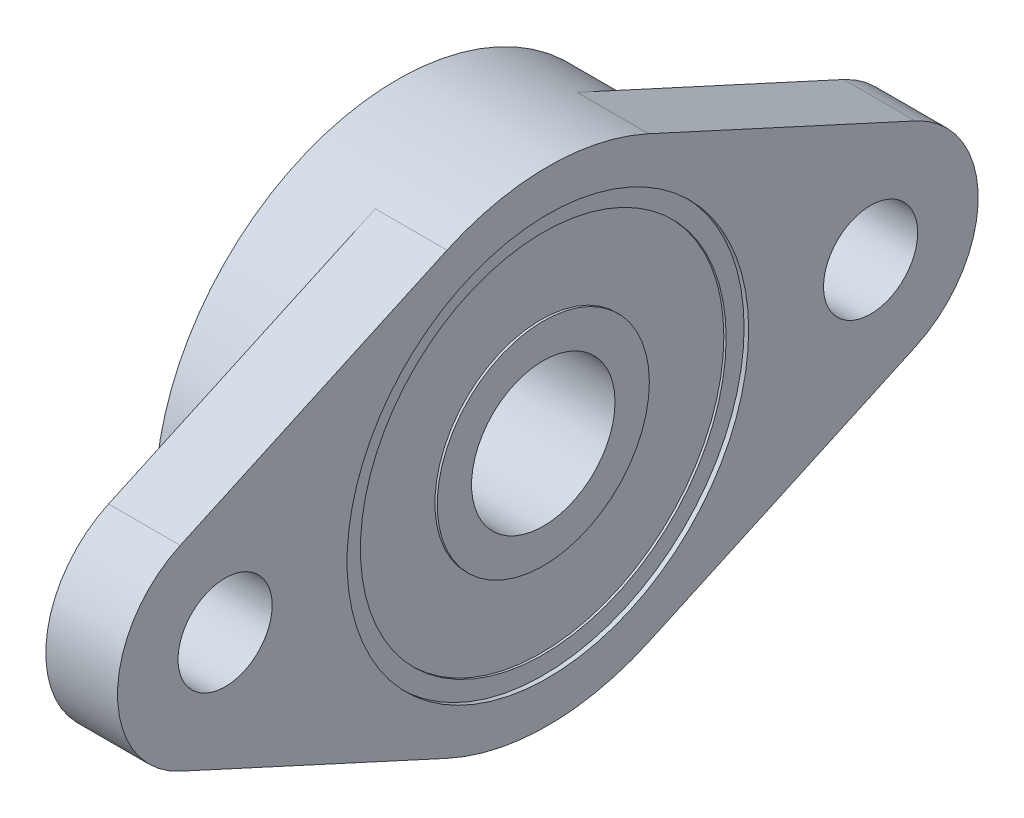
SolidWorks part; units mm, degrees
ref_plane "Front Plane" through (0, 0, 0) normal (0, 0, 1) x (1, 0, 0)
ref_plane "Top Plane" through (0, 0, 0) normal (0, 1, 0) x (1, 0, 0)
ref_plane "Right Plane" through (0, 0, 0) normal (1, 0, 0) x (0, 0, -1)
sketch "Sketch2" plane through (0, 0, 0) normal (0, 1, 0) x (1, 0, 0)
  line L0 (0, 0) -> (-21.1446, 0) construction
  line L1 (-0.2554, 4) -> (-11.7, 4)
  line L2 (-11.7, 4) -> (-11.7, 5.915)
  line L3 (-11.7, 5.915) -> (-7.6784, 5.915)
  line L4 (-7.6784, 5.915) -> (-7.6784, 10.2)
  line L5 (-7.6784, 10.2) -> (-7.9154, 10.2)
  line L6 (-7.9154, 10.2) -> (-7.9154, 11.2)
  line L7 (-7.9154, 11.2) -> (-8.1271, 11.2)
  line L8 (-8.1271, 11.2) -> (-8.4, 11.4729)
  line L9 (-8.4, 11.4729) -> (-8.4, 13.5)
  line L10 (-8.4, 13.5) -> (0, 13.5)
  line L12 (0, 0) -> (0, 13.5) construction
  line L13 (-7.6784, 5.915) -> (4.6554, 5.915) construction
  line L14 (-7.6784, 10.2) -> (4.6554, 10.2) construction
  line L15 (-7.9154, 11.2) -> (4.6554, 11.2) construction
  line L16 (-0.2554, 4) -> (-0.2554, 5.915)
  line L17 (-0.2554, 5.915) -> (-0.3846, 5.915)
  line L18 (-0.3846, 5.915) -> (-0.3846, 10.2)
  line L19 (-0.3846, 10.2) -> (-0.2554, 10.2)
  line L20 (-0.2554, 10.2) -> (-0.2554, 11.2)
  line L21 (-0.2554, 11.2) -> (0, 11.2)
  line L22 (0, 11.2) -> (0, 13.5)
  dimension "D1" = 8
  dimension "D2" = 11.7
  dimension "D3" = 8.4
  dimension "D4" = 27
  dimension "D5" = 11.83
  dimension "D6" = 1
  dimension "D7" = 2.3
revolve "Revolve1" add sketch "Sketch2" angle 360 about L0
sketch "Sketch4" plane through (0, 0, 0) normal (1, 0, 0) x (0, 0, -1)
  line L0 (0, 20.3331) -> (0, -26.3104) construction
  line L1 (18, 0) -> (-18, 0) construction
  line L2 (-5.625, 12.2723) -> (-20.5, 5.4544)
  line L3 (-20.5, -5.4544) -> (-5.625, -12.2723)
  line L4 (-20.5, 5.4544) -> (-5.625, 12.2723)
  line L5 (-5.625, -12.2723) -> (-20.5, -5.4544)
  line L6 (5.625, -12.2723) -> (20.5, -5.4544)
  line L7 (20.5, 5.4544) -> (5.625, 12.2723)
  line L8 (20.5, -5.4544) -> (5.625, -12.2723)
  line L9 (5.625, 12.2723) -> (20.5, 5.4544)
  circle A0 centre (-18, 0) radius 2.625
  arc A1 (-20.5, 5.4544) -> (-20.5, -5.4544) centre (-18, 0) ccw
  circle A3 centre (0, 0) radius 13.5 construction
  arc A4 (-5.625, -12.2723) -> (5.625, -12.2723) centre (0, 0) ccw
  arc A5 (5.625, 12.2723) -> (-5.625, 12.2723) centre (0, 0) ccw
  arc A6 (5.625, -12.2723) -> (-5.625, -12.2723) centre (0, 0) cw
  arc A7 (-5.625, 12.2723) -> (5.625, 12.2723) centre (0, 0) cw
  arc A8 (20.5, 5.4544) -> (20.5, -5.4544) centre (18, 0) cw
  circle A9 centre (18, 0) radius 2.625
  circle A10 centre (0, 0) radius 11.2
  point P8 (-24, 0)
  point P19 (24, 0)
  dimension "D2" = 5.25
  dimension "D1" = 36
  dimension "D3" = 48
extrude "Boss-Extrude3" add sketch "Sketch4" against normal blind 4 contours A8 L7 A5 L2 A1 L3 A4 L6 A10 A0 A9
